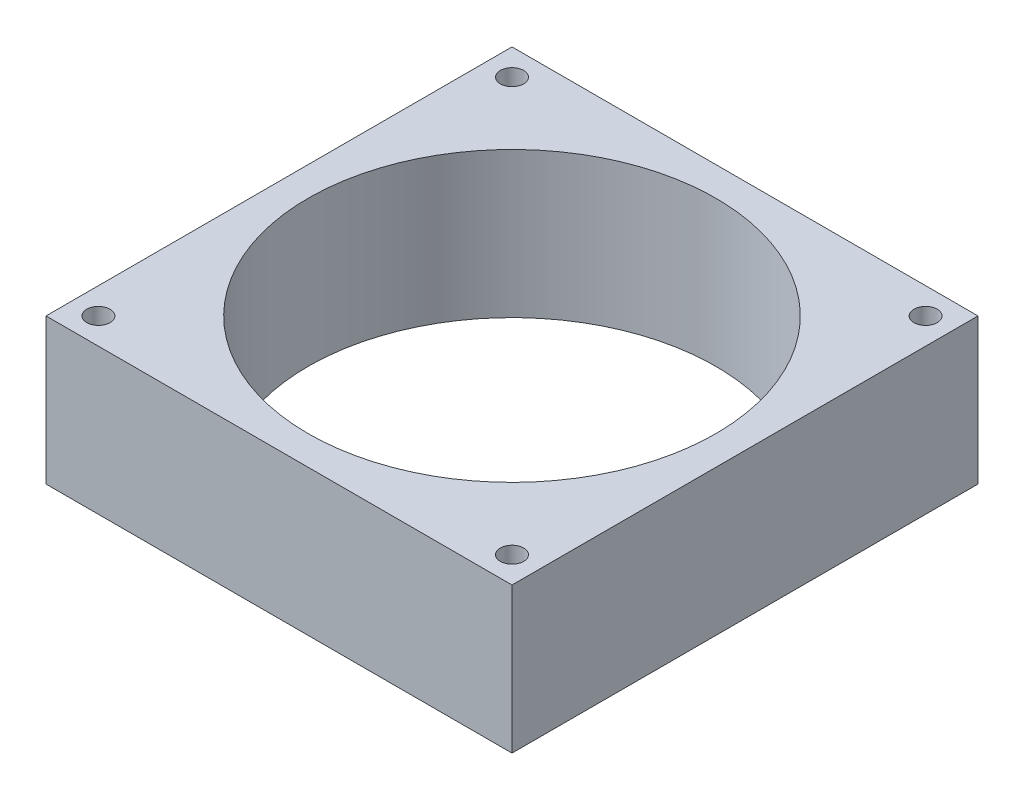
SolidWorks part; units mm, degrees
ref_plane "Front Plane" through (0, 0, 0) normal (0, 0, 1) x (1, 0, 0)
ref_plane "Top Plane" through (0, 0, 0) normal (0, 1, 0) x (1, 0, 0)
ref_plane "Right Plane" through (0, 0, 0) normal (1, 0, 0) x (0, 0, -1)
sketch "Sketch1" plane through (0, 0, 0) normal (0, 1, 0) x (1, 0, 0)
  line L1 (-40, -40) -> (40, -40)
  line L2 (-40, -40) -> (-40, 40)
  line L3 (-40, 40) -> (40, 40)
  line L4 (40, -40) -> (40, 40)
  line L5 (-40, -40) -> (40, 40) construction
  line L6 (-40, 40) -> (40, -40) construction
  line L11 (35.5, -35.5) -> (-35.5, 35.5) construction
  line L12 (35.5, 35.5) -> (-35.5, -35.5) construction
  circle A0 centre (-35.5, 35.5) radius 2
  circle A1 centre (35.5, 35.5) radius 2
  circle A2 centre (35.5, -35.5) radius 2
  circle A3 centre (-35.5, -35.5) radius 2
  circle A4 centre (0, 0) radius 35
  point P0 (0, 0)
  point P6 (0, 0)
  dimension "D4" = 4
  dimension "D7" = 70
  dimension "D1" = 80
  dimension "D2" = 80
  dimension "D3" = 71
  dimension "D5" = 2
  dimension "D6" = 2
extrude "Boss-Extrude1" add sketch "Sketch1" along normal blind 25
